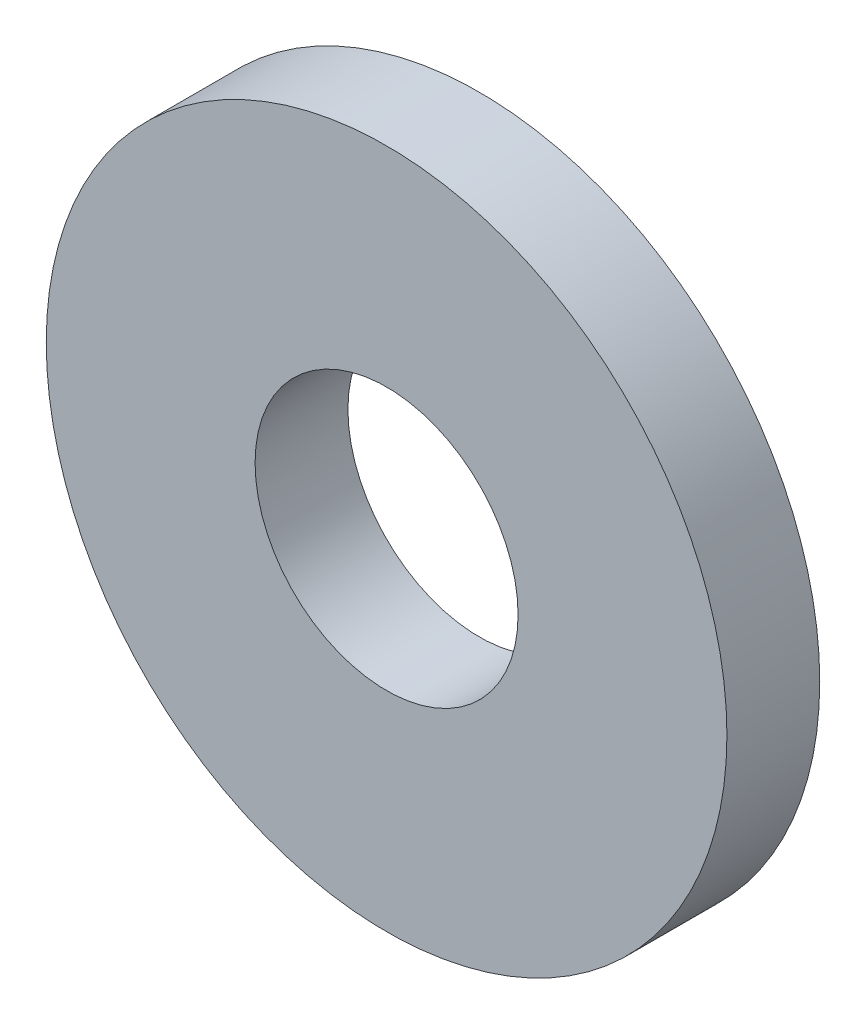
SolidWorks part; units mm, degrees
ref_plane "Alzado" through (0, 0, 0) normal (0, 0, 1) x (1, 0, 0)
ref_plane "Planta" through (0, 0, 0) normal (0, 1, 0) x (1, 0, 0)
ref_plane "Vista lateral" through (0, 0, 0) normal (1, 0, 0) x (0, 0, -1)
sketch "Croquis1" plane through (0, 0, 0) normal (0, 0, 1) x (1, 0, 0)
  circle A0 centre (0, 0) radius 4.25
  circle A1 centre (0, 0) radius 11
  dimension "D1" = 8.5
  dimension "D2" = 22
extrude "Saliente-Extruir1" add sketch "Croquis1" against normal blind 3
